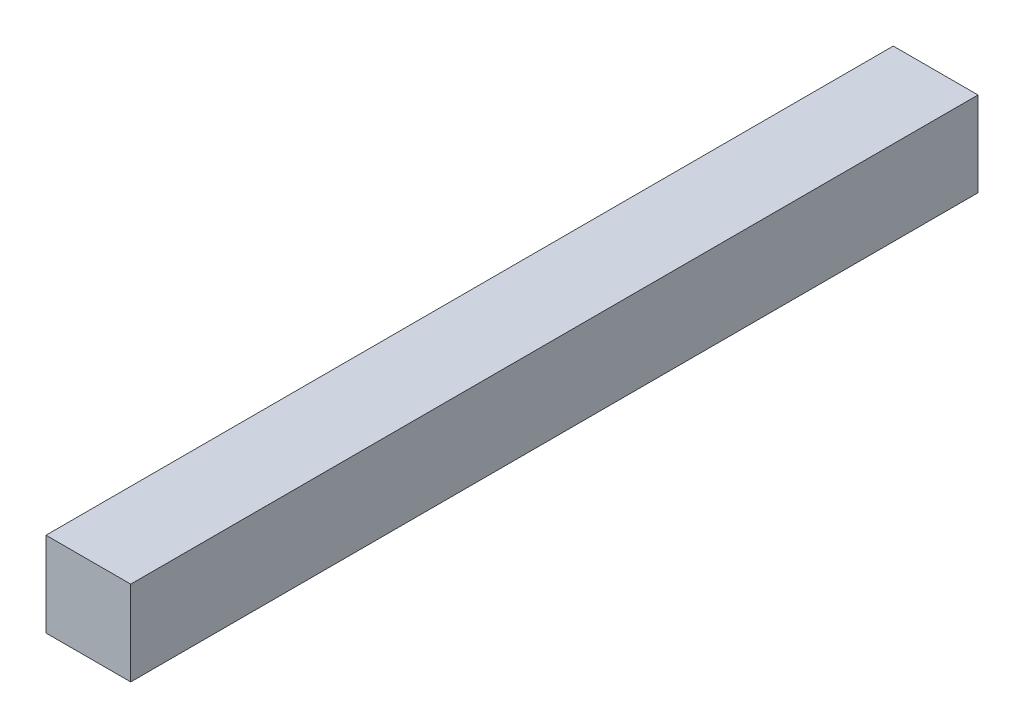
SolidWorks part; units mm, degrees
ref_plane "Front Plane" through (0, 0, 0) normal (0, 0, 1) x (1, 0, 0)
ref_plane "Top Plane" through (0, 0, 0) normal (0, 1, 0) x (1, 0, 0)
ref_plane "Right Plane" through (0, 0, 0) normal (1, 0, 0) x (0, 0, -1)
sketch "Sketch1" plane through (0, 0, 0) normal (0, 0, 1) x (1, 0, 0)
  line L1 (-13.5667, -1.4644) -> (11.8333, -1.4644)
  line L2 (-13.5667, -1.4644) -> (-13.5667, -26.8644)
  line L3 (-13.5667, -26.8644) -> (11.8333, -26.8644)
  line L4 (11.8333, -1.4644) -> (11.8333, -26.8644)
  dimension "D1" = 25.4
  dimension "D2" = 25.4
extrude "Boss-Extrude1" add sketch "Sketch1" along normal blind 254
